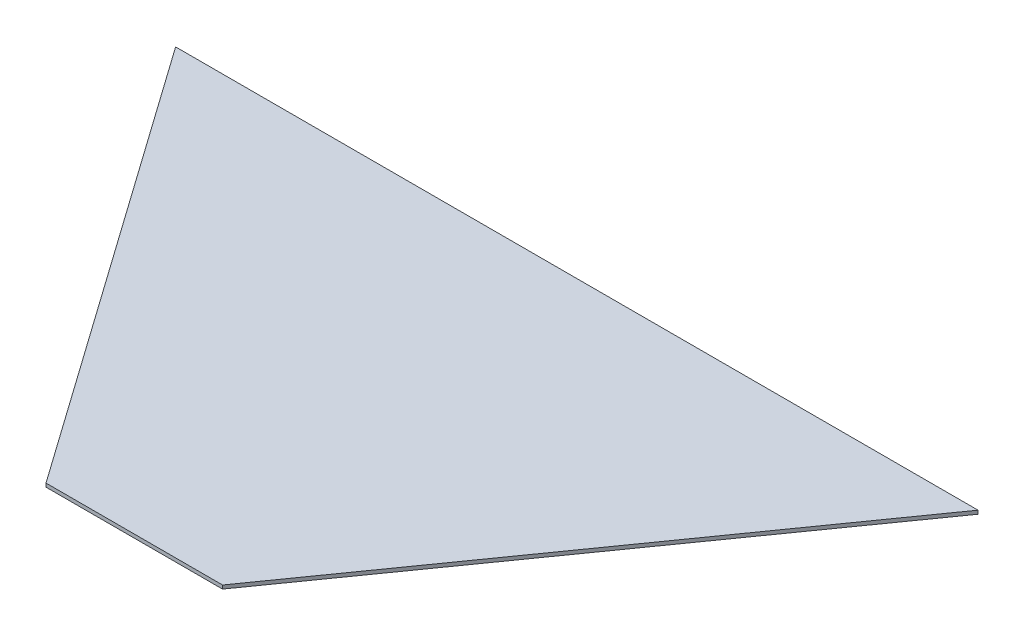
SolidWorks part; units mm, degrees
ref_plane "Front Plane" through (0, 0, 0) normal (0, 0, 1) x (1, 0, 0)
ref_plane "Top Plane" through (0, 0, 0) normal (0, 1, 0) x (1, 0, 0)
ref_plane "Right Plane" through (0, 0, 0) normal (1, 0, 0) x (0, 0, -1)
sketch "Sketch1" plane through (0, 0, 0) normal (0, 1, 0) x (1, 0, 0)
  line L0 (-168.1105, 185.4369) -> (-36.9868, 0)
  line L1 (168.1105, 185.4369) -> (-168.1105, 185.4369)
  line L3 (36.9868, 0) -> (-36.9868, 0)
  line L5 (168.1105, 185.4369) -> (36.9868, 0)
  line L6 (0, 0) -> (0, 185.4369) construction
  point P9 (0, 185.4369)
  dimension "Base" = 73.9737
  dimension "D1" = 336.2211
  dimension "D2" = 185.4369
extrude "Boss-Extrude1" add sketch "Sketch1" along normal blind 1.5
equation "\"base\" = \"width\" / 3 - 1.5in"
equation "\"Base@Sketch1\"= \"base\""
equation "\"height\"= 60"
equation "\"angle\"= 45deg"
equation "\"width\"= 13.23705in"
equation "\"D1@Sketch1\"=\"width\""
equation "\"D2@Sketch1\"=(\"width\"-\"base\")/2/sin(\"angle\")"
